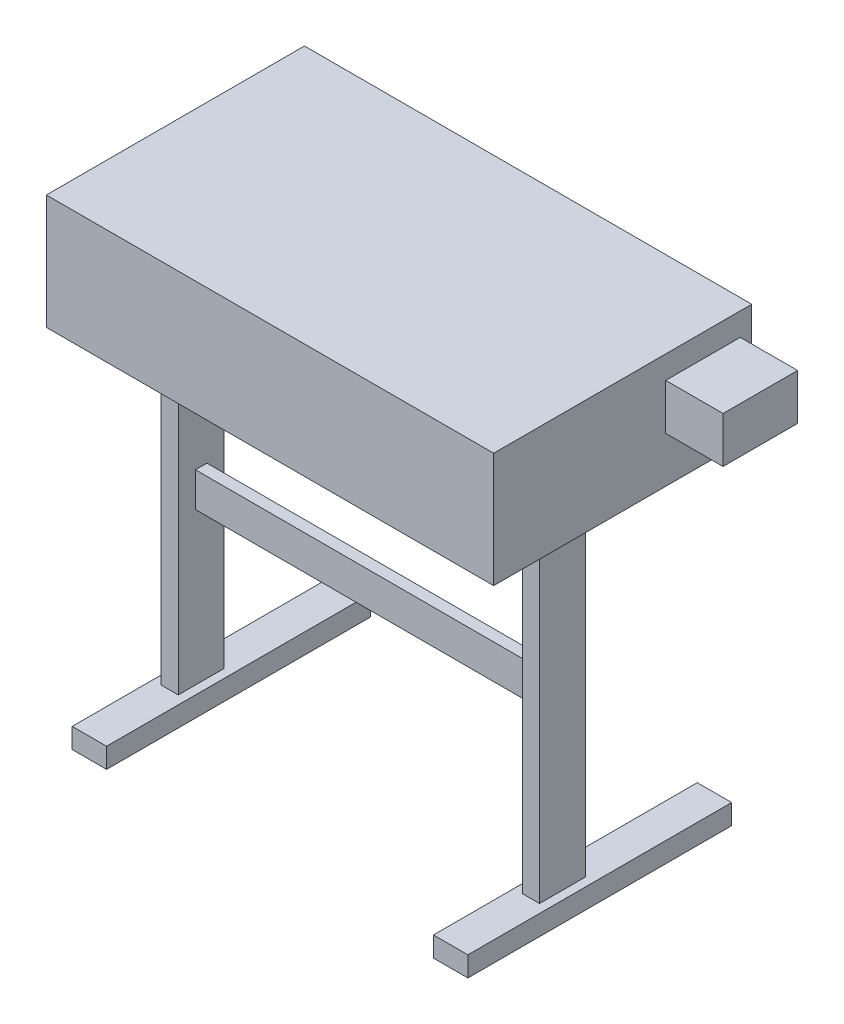
SolidWorks part; units mm, degrees
ref_plane "Front Plane" through (0, 0, 0) normal (0, 0, 1) x (1, 0, 0)
ref_plane "Top Plane" through (0, 0, 0) normal (0, 1, 0) x (1, 0, 0)
ref_plane "Right Plane" through (0, 0, 0) normal (1, 0, 0) x (0, 0, -1)
sketch "Sketch1" plane through (0, 0, 0) normal (0, 1, 0) x (1, 0, 0)
  line L1 (-495.3, 0) -> (495.3, 0)
  line L2 (-495.3, 0) -> (-495.3, -571.5)
  line L3 (-495.3, -571.5) -> (495.3, -571.5)
  line L4 (495.3, 0) -> (495.3, -571.5)
  dimension "D1" = 990.6
  dimension "D2" = 571.5
extrude "Boss-Extrude1" add sketch "Sketch1" along normal blind 254
sketch "Sketch3" plane through (495.3, 0, 0) normal (1, 0, 0) x (0, 0, -1)
  line L0 (-571.5, 0) -> (0, 0) construction
  line L1 (-190.5, 203.2) -> (-25.4, 203.2)
  line L2 (-190.5, 203.2) -> (-190.5, 101.6)
  line L3 (-190.5, 101.6) -> (-25.4, 101.6)
  line L4 (-25.4, 203.2) -> (-25.4, 101.6)
  line L5 (0, 254) -> (0, 0) construction
  dimension "D1" = 165.1
  dimension "D2" = 101.6
  dimension "D3" = 101.6
  dimension "D4" = 25.4
extrude "Boss-Extrude2" add sketch "Sketch3" along normal blind 127
sketch "Sketch4" plane through (0, 0, 0) normal (0, 1, 0) x (1, 0, 0)
  line L0 (0, -71.7728) -> (0, -343.6641) construction
  line L1 (495.3, 0) -> (-495.3, 0) construction
  line L2 (381, -393.7) -> (419.1, -393.7)
  line L3 (381, -393.7) -> (381, -292.1)
  line L4 (381, -292.1) -> (419.1, -292.1)
  line L5 (419.1, -393.7) -> (419.1, -292.1)
  line L6 (-419.1, -393.7) -> (-381, -393.7)
  line L7 (-419.1, -393.7) -> (-419.1, -292.1)
  line L8 (-419.1, -292.1) -> (-381, -292.1)
  line L9 (-381, -393.7) -> (-381, -292.1)
  dimension "D1" = 101.6
  dimension "D2" = 38.1
  dimension "D3" = 762
  dimension "D4" = 292.1
extrude "Boss-Extrude3" add sketch "Sketch4" against normal blind 781.05 separate body
sketch "Sketch5" plane through (381, 0, 0) normal (-1, 0, 0) x (0, 0, 1)
  line L0 (342.9, -726.0261) -> (342.9, -299.3268) construction
  line L1 (292.1, -781.05) -> (292.1, 0) construction
  line L2 (330.2, -323.85) -> (355.6, -323.85)
  line L3 (330.2, -323.85) -> (330.2, -400.05)
  line L4 (330.2, -400.05) -> (355.6, -400.05)
  line L5 (355.6, -323.85) -> (355.6, -400.05)
  line L6 (393.7, -781.05) -> (393.7, 0) construction
  line L7 (292.1, -781.05) -> (393.7, -781.05) construction
  dimension "D1" = 25.4
  dimension "D2" = 76.2
  dimension "D3" = 381
extrude "Boss-Extrude4" add sketch "Sketch5" along normal up to surface (762 mm away) up to face at (-381, -390.525, 342.9)
sketch "Sketch6" plane through (0, -781.05, 0) normal (0, -1, 0) x (1, 0, 0)
  line L0 (400.05, 425.3534) -> (400.05, 638.7209) construction
  line L1 (361.95, 571.5) -> (438.15, 571.5)
  line L2 (361.95, 571.5) -> (361.95, -12.7)
  line L3 (361.95, -12.7) -> (438.15, -12.7)
  line L4 (438.15, 571.5) -> (438.15, -12.7)
  line L5 (-438.15, 571.5) -> (-361.95, 571.5)
  line L6 (-438.15, 571.5) -> (-438.15, -12.7)
  line L7 (-438.15, -12.7) -> (-361.95, -12.7)
  line L8 (-361.95, 571.5) -> (-361.95, -12.7)
  line L9 (-400.05, 608.2399) -> (-400.05, 717.9718) construction
  line L10 (381, 292.1) -> (381, 393.7) construction
  line L11 (419.1, 393.7) -> (419.1, 292.1) construction
  line L12 (-419.1, 292.1) -> (-419.1, 393.7) construction
  line L13 (-381, 393.7) -> (-381, 292.1) construction
  line L14 (381, 393.7) -> (419.1, 393.7) construction
  dimension "D1" = 76.2
  dimension "D2" = 584.2
  dimension "D3" = 177.8
extrude "Boss-Extrude5" add sketch "Sketch6" against normal blind 44.45
